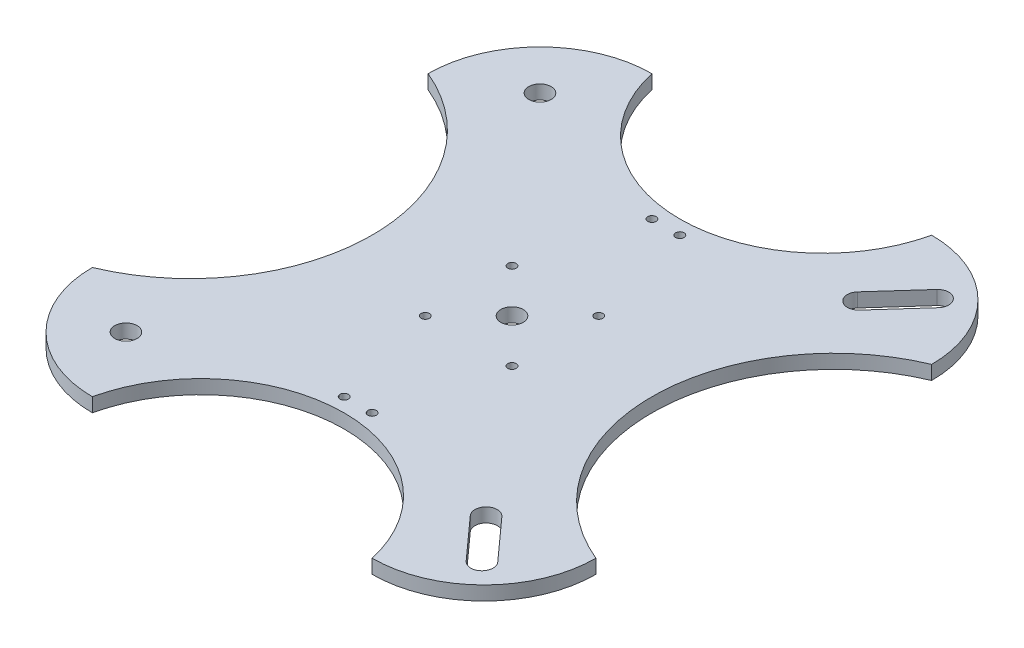
SolidWorks part; units mm, degrees
ref_plane "Piano frontale" through (0, 0, 0) normal (0, 0, 1) x (1, 0, 0)
ref_plane "Piano superiore" through (0, 0, 0) normal (0, 1, 0) x (1, 0, 0)
ref_plane "Piano destro" through (0, 0, 0) normal (1, 0, 0) x (0, 0, -1)
sketch "Schizzo1" plane through (0, 0, 0) normal (0, 1, 0) x (1, 0, 0)
  line L0 (-90, 100) -> (-50, 100) construction
  line L1 (-90, 100) -> (90, 100) construction
  line L2 (-90, 100) -> (-90, -100) construction
  line L3 (-90, -100) -> (90, -100) construction
  line L4 (90, 100) -> (90, -100) construction
  line L5 (90, 100) -> (50, 100) construction
  line L6 (-90, 100) -> (-90, 60) construction
  line L7 (90, 100) -> (90, 60) construction
  line L8 (-90, -100) -> (-90, -60) construction
  line L9 (-90, -100) -> (-50, -100) construction
  line L10 (90, -100) -> (50, -100) construction
  line L11 (90, -100) -> (90, -60) construction
  line L12 (-50, 100) -> (-50, -100) construction
  line L13 (-90, -60) -> (90, -60) construction
  line L14 (-90, 60) -> (90, 60) construction
  line L15 (50, 100) -> (50, -100) construction
  line L16 (-90, 100) -> (90, -100) construction
  line L17 (-90, -100) -> (90, 100) construction
  line L18 (-64, 74) -> (64, -74) construction
  line L19 (-64, -74) -> (64, 74) construction
  line L20 (73.6628, -78.7571) -> (60.2835, -63.8912)
  line L21 (67.7165, -84.1088) -> (54.3372, -69.2429)
  line L22 (61.0268, -76.6759) -> (66.9732, -71.3241) construction
  line L23 (60.2835, 63.8912) -> (73.6628, 78.7571)
  line L24 (54.3372, 69.2429) -> (67.7165, 84.1088)
  line L25 (61.0268, 76.6759) -> (66.9732, 71.3241) construction
  arc A0 (-50, 100) -> (-90, 60) centre (-50, 60) ccw
  arc A1 (50, 100) -> (90, 60) centre (50, 60) cw
  arc A2 (90, -60) -> (50, -100) centre (50, -60) cw
  arc A3 (-50, -100) -> (-90, -60) centre (-50, -60) cw
  arc A4 (-90, 60) -> (-90, -60) centre (-115, 0) cw
  arc A5 (90, 60) -> (90, -60) centre (115, 0) ccw
  arc A6 (50, -100) -> (-50, -100) centre (0, -111.25) ccw
  arc A7 (50, 100) -> (-50, 100) centre (0, 111.25) cw
  circle A8 centre (-64, 74) radius 4
  circle A9 centre (64, 74) radius 4 construction
  circle A10 centre (64, -74) radius 4 construction
  circle A11 centre (-64, -74) radius 4
  circle A12 centre (0, 0) radius 4
  arc A13 (60.2835, -63.8912) -> (54.3372, -69.2429) centre (57.3104, -66.5671) ccw
  arc A14 (73.6628, -78.7571) -> (67.7165, -84.1088) centre (70.6896, -81.4329) cw
  arc A15 (73.6628, 78.7571) -> (67.7165, 84.1088) centre (70.6896, 81.4329) ccw
  arc A16 (60.2835, 63.8912) -> (54.3372, 69.2429) centre (57.3104, 66.5671) cw
  dimension "D4" = 8
  dimension "D5" = 14
  dimension "D6" = 14
  dimension "D7" = 14
  dimension "D8" = 14
  dimension "D9" = 14
  dimension "D10" = 14
  dimension "D11" = 14
  dimension "D12" = 14
  dimension "D13" = 8
  dimension "D1" = 180
  dimension "D2" = 200
  dimension "D3" = 40
  dimension "D14" = 8
  dimension "D15" = 20
  dimension "D16" = 20
extrude "Estrusione-Estrusione1" add sketch "Schizzo1" along normal blind 5
sketch "Schizzo2" plane through (0, 5, 0) normal (0, 1, 0) x (1, 0, 0)
  line L0 (-15.5, 15.5) -> (-15.5, -15.5) construction
  line L1 (-15.5, -15.5) -> (15.5, -15.5) construction
  line L2 (15.5, -15.5) -> (15.5, 15.5) construction
  line L3 (15.5, 15.5) -> (-15.5, 15.5) construction
  circle A0 centre (-15.5, 15.5) radius 1.5
  circle A1 centre (15.5, 15.5) radius 1.5
  circle A2 centre (15.5, -15.5) radius 1.5
  circle A3 centre (-15.5, -15.5) radius 1.5
  circle A4 centre (0, 0) radius 4 construction
  dimension "D2" = 3
  dimension "D1" = 31
  dimension "D3" = 15.5
  dimension "D4" = 15.5
extrude "Taglio-Estrusione1" cut sketch "Schizzo2" against normal through all
sketch "Schizzo3" plane through (0, 5, 0) normal (0, 1, 0) x (1, 0, 0)
  line L0 (0, -96.1941) -> (0, 108.5349) construction
  circle A0 centre (-5, 55) radius 1.5
  circle A1 centre (5, 55) radius 1.5
  circle A2 centre (-5, -55) radius 1.5
  circle A3 centre (5, -55) radius 1.5
  circle A5 centre (0, 0) radius 4 construction
  dimension "D2" = 3
  dimension "D4" = 10
  dimension "D5" = 5
  dimension "D6" = 55
  dimension "D7" = 55
  dimension "D8" = 55
  dimension "D1" = 10
  dimension "D3" = 5
extrude "Taglio-Estrusione2" cut sketch "Schizzo3" against normal through all
